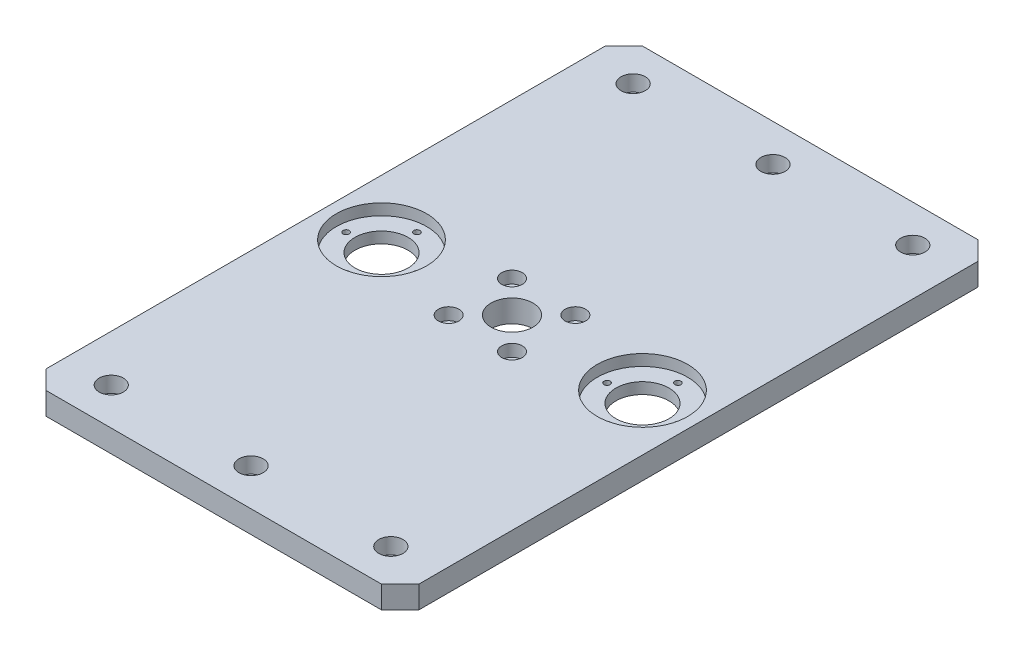
SolidWorks part; units mm, degrees
ref_plane "前视基准面" through (0, 0, 0) normal (0, 0, 1) x (1, 0, 0)
ref_plane "上视基准面" through (0, 0, 0) normal (0, 1, 0) x (1, 0, 0)
ref_plane "右视基准面" through (0, 0, 0) normal (1, 0, 0) x (0, 0, -1)
sketch "草图1" plane through (0, 0, 0) normal (0, 1, 0) x (1, 0, 0)
  line L1 (-100, 160) -> (100, 160)
  line L2 (-100, 160) -> (-100, -160)
  line L3 (-100, -160) -> (100, -160)
  line L4 (100, 160) -> (100, -160)
  line L5 (-100, 160) -> (100, -160) construction
  line L6 (-100, -160) -> (100, 160) construction
  point P0 (0, 0)
  dimension "D1" = 320
  dimension "D2" = 200
extrude "凸台-拉伸1" add sketch "草图1" along normal blind 12
hole_wizard "打孔尺寸(%根据)内六角圆柱头螺钉的类型2" positions "草图3" profile "草图2" counterbore size "M8" standard "GB" end condition through all
sketch "草图3" plane through (0, 12, 0) normal (0, 1, 0) x (1, 0, 0)
  line L0 (0, 160) -> (0, -160) construction
  line L1 (100, 160) -> (-100, 160) construction
  line L2 (-100, -160) -> (100, -160) construction
  line L4 (-100, 0) -> (100, 0) construction
  line L5 (-100, 160) -> (-100, -160) construction
  line L6 (100, -160) -> (100, 160) construction
  point P0 (-75, 140)
  point P20 (75, 140)
  point P21 (75, -140)
  point P22 (-75, -140)
  point P24 (0, 140)
  point P27 (0, -140)
  dimension "D1" = 150
  dimension "D2" = 280
sketch "草图2" plane through (-75, 12, -140) normal (1, 0, 0) x (0, 0, 1)
  line L0 (0, 0) -> (0, 12)
  line L1 (0, 12) -> (4.25, 12)
  line L3 (4.25, 12) -> (4.25, 8.5)
  line L4 (4.25, 8.5) -> (6.5, 8.5)
  line L5 (6.5, 8.5) -> (6.5, 0)
  line L7 (6.5, 0) -> (0, 0)
  line L11 (0, -6.35) -> (0, 107.95) construction
  dimension "通孔孔直径" = 8.5
  dimension "通孔孔深度" = 12
  dimension "柱形沉头孔直径" = 13
  dimension "柱形沉头孔深度" = 8.5
chamfer "倒角1" distance 10 angle 45 4 edges at (-100, 6, -160) (100, 6, -160) (100, 6, 160) (-100, 6, 160)
sketch "草图4" plane through (0, 0, 0) normal (0, -1, 0) x (-1, 0, 0)
  line L0 (100, 0) -> (-100, 0) construction
  line L1 (100, 150) -> (100, -150) construction
  line L2 (-100, -150) -> (-100, 150) construction
  line L3 (0, 160) -> (0, -160) construction
  line L4 (-90, 160) -> (90, 160) construction
  line L5 (90, -160) -> (-90, -160) construction
  circle A0 centre (0, 0) radius 11.25
  dimension "D1" = 22.5
extrude "切除-拉伸1" cut sketch "草图4" against normal through all
hole_wizard "打孔尺寸(%根据)内六角圆柱头螺钉的类型2" positions "草图6" profile "草图5" counterbore size "M6" standard "GB" end condition through all
sketch "草图6" plane through (0, 12, 0) normal (0, 1, 0) x (1, 0, 0)
  line L0 (-100, 0) -> (100, 0) construction
  line L1 (-100, 150) -> (-100, -150) construction
  line L2 (100, -150) -> (100, 150) construction
  line L4 (0, 160) -> (0, -160) construction
  line L5 (90, 160) -> (-90, 160) construction
  line L6 (-90, -160) -> (90, -160) construction
  point P0 (-17, 17)
  point P19 (-17, -17)
  point P20 (17, -17)
  point P21 (17, 17)
  dimension "D1" = 34
  dimension "D2" = 34
sketch "草图5" plane through (-17, 12, -17) normal (1, 0, 0) x (0, 0, 1)
  line L0 (0, 0) -> (0, 12)
  line L1 (0, 12) -> (3.25, 12)
  line L3 (3.25, 12) -> (3.25, 6.5)
  line L4 (3.25, 6.5) -> (5.5, 6.5)
  line L5 (5.5, 6.5) -> (5.5, 0)
  line L7 (5.5, 0) -> (0, 0)
  line L11 (0, -6.35) -> (0, 107.95) construction
  dimension "通孔孔直径" = 6.5
  dimension "通孔孔深度" = 12
  dimension "柱形沉头孔直径" = 11
  dimension "柱形沉头孔深度" = 6.5
sketch "草图7" plane through (0, 12, 0) normal (0, 1, 0) x (1, 0, 0)
  line L0 (-100, 0) -> (100, 0) construction
  line L1 (-100, 150) -> (-100, -150) construction
  line L2 (100, -150) -> (100, 150) construction
  line L3 (0, 160) -> (0, -160) construction
  line L4 (90, 160) -> (-90, 160) construction
  line L5 (-90, -160) -> (90, -160) construction
  line L6 (-70, 24.25) -> (-70, -24.25) construction
  circle A0 centre (-70, 0) radius 24.25
  circle A1 centre (70, 0) radius 24.25
  dimension "D1" = 48.5
  dimension "D2" = 140
extrude "切除-拉伸2" cut sketch "草图7" against normal blind 6
sketch "草图8" plane through (0, 6, 0) normal (0, 1, 0) x (1, 0, 0)
  line L0 (0, 160) -> (0, -160) construction
  line L1 (90, 160) -> (-90, 160) construction
  line L2 (-90, -160) -> (90, -160) construction
  circle A0 centre (-70, 0) radius 14.25
  circle A1 centre (70, 0) radius 14.25
  dimension "D1" = 28.5
extrude "切除-拉伸3" cut sketch "草图8" against normal through all
hole_wizard "M4 螺纹孔1" positions "草图12" profile "草图11" tap size "M4" standard "GB" end condition through all
sketch "草图12" plane through (0, 12, 0) normal (0, 1, 0) x (1, 0, 0)
  line L0 (-70, 24.25) -> (-70, -24.25) construction
  line L2 (-94.25, 0) -> (-45.75, 0) construction
  line L3 (0, 160) -> (0, -160) construction
  line L4 (90, 160) -> (-90, 160) construction
  line L5 (-90, -160) -> (90, -160) construction
  line L7 (94.25, 0) -> (45.75, 0) construction
  line L8 (70, 24.25) -> (70, -24.25) construction
  circle A0 centre (-70, 0) radius 19 construction
  circle A1 centre (-70, 0) radius 24.25 construction
  circle A2 centre (-70, 0) radius 24.25 construction
  circle A3 centre (70, 0) radius 19 construction
  point P18 (-70, 19)
  point P20 (-89, 0)
  point P22 (-70, -19)
  point P24 (-51, 0)
  point P40 (51, 0)
  point P41 (70, -19)
  point P42 (89, 0)
  point P43 (70, 19)
  dimension "D1" = 38
sketch "草图11" plane through (-70, 12, -19) normal (1, 0, 0) x (0, 0, 1)
  line L0 (0, 0) -> (0, 12)
  line L1 (0, 12) -> (1.65, 12)
  line L2 (1.65, 12) -> (1.65, 0)
  line L5 (1.65, 0) -> (0, 0)
  line L11 (0, -6.35) -> (0, 107.95) construction
  dimension "通孔螺纹孔钻头直径" = 3.3
  dimension "通孔螺纹孔钻头深度" = 12
cosmetic thread "孔螺蚊线1" parameters "D2"=4
cosmetic thread "孔螺蚊线2" parameters "D2"=4
cosmetic thread "孔螺蚊线3" parameters "D2"=4
cosmetic thread "孔螺蚊线4" parameters "D2"=4
cosmetic thread "孔螺蚊线5" parameters "D2"=4
cosmetic thread "孔螺蚊线6" parameters "D2"=4
cosmetic thread "孔螺蚊线7" parameters "D2"=4
cosmetic thread "孔螺蚊线8" parameters "D2"=4
